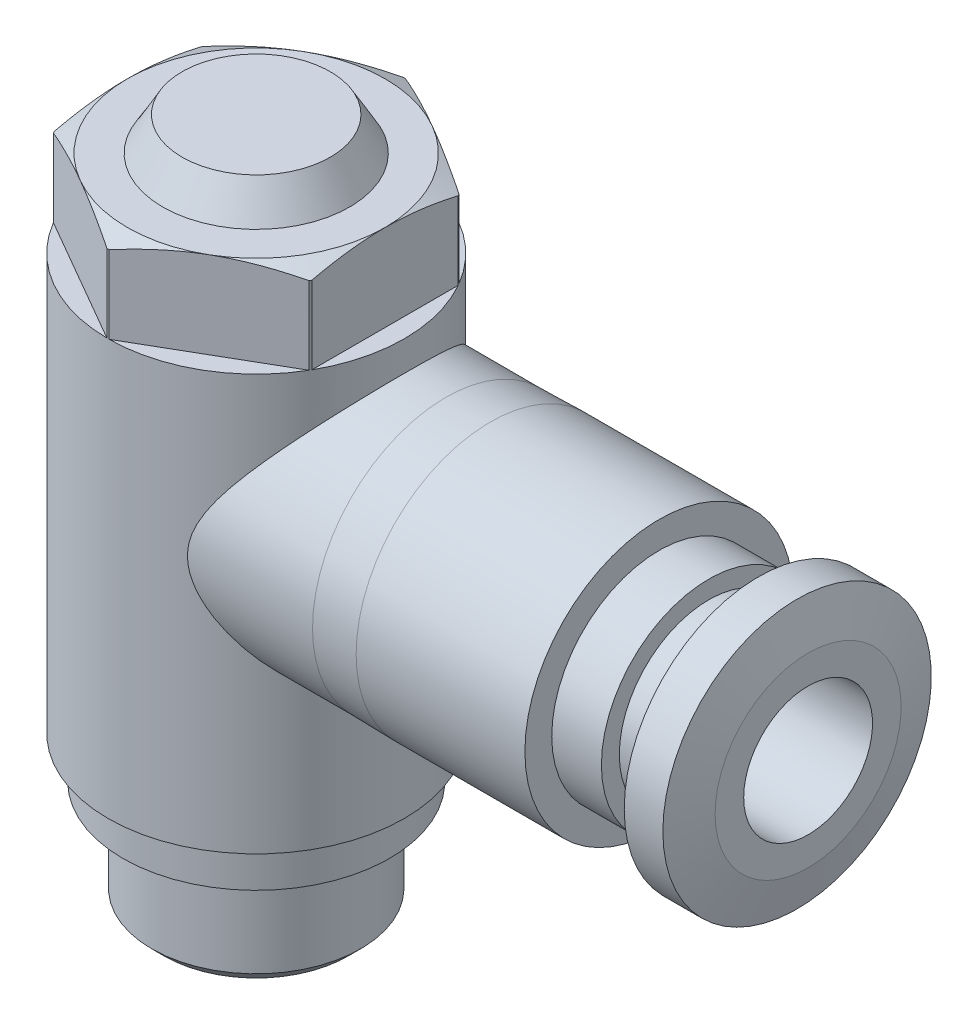
SolidWorks part; units mm, degrees
material "Kunststoff schwarz"
ref_plane "Vorne" through (0, 0, 0) normal (0, 0, 1) x (1, 0, 0)
ref_plane "Oben" through (0, 0, 0) normal (0, 1, 0) x (1, 0, 0)
ref_plane "Rechts" through (0, 0, 0) normal (1, 0, 0) x (0, 0, -1)
ref_plane "Ebene1" through (0, 0, 0) normal (0, 0, 1) x (1, 0, 0)
sketch "Skizze1" plane through (0, 0, 0) normal (0, 0, 1) x (1, 0, 0)
  line L0 (0, 13.2) -> (3.45, 13.2)
  line L1 (3.45, 13.2) -> (4.3508, 11.6398)
  line L2 (4.3508, 11.6398) -> (6, 11.6398)
  line L3 (6, 11.6398) -> (6.9, 11.2201)
  line L4 (6.9, 11.2201) -> (6.9, -11.7429)
  line L5 (6.9, -11.7429) -> (6.21, -11.7429)
  line L6 (6.21, -11.7429) -> (6.21, -13.7)
  line L7 (6.21, -13.7) -> (4.864, -13.7)
  line L8 (4.864, -13.7) -> (4.864, -18.019)
  line L9 (4.864, -18.019) -> (4.283, -18.6)
  line L10 (4.283, -18.6) -> (3.648, -18.6)
  line L11 (3.648, -18.6) -> (3.648, -8.872)
  line L12 (3.648, -8.872) -> (0, -8.872)
  line L13 (0, -8.872) -> (0, 13.2)
  line L14 (0, -18.6) -> (0, 13.2) construction
revolve "Rotation1" add sketch "Skizze1" angle 360 about L14
ref_plane "Ebene2" through (0, 11.6398, 0) normal (0, 1, 0) x (-1, 0, 0)
sketch "Skizze2" plane through (0, 11.6398, 0) normal (0, 1, 0) x (-1, 0, 0)
  line L0 (7.8, -4.5033) -> (7.8, 4.5033)
  line L1 (7.8, 4.5033) -> (0, 9.0067)
  line L2 (0, 9.0067) -> (-7.8, 4.5033)
  line L3 (-7.8, 4.5033) -> (-7.8, -4.5033)
  line L4 (-7.8, -4.5033) -> (-0.05, -8.9778)
  line L5 (-0.05, -8.9778) -> (-0.05, -6.8993)
  line L6 (-0.05, -6.8993) -> (-6, -3.4641)
  line L7 (-6, -3.4641) -> (-6, 3.4641)
  line L8 (-6, 3.4641) -> (0, 6.9282)
  line L9 (0, 6.9282) -> (6, 3.4641)
  line L10 (6, 3.4641) -> (6, -3.4641)
  line L11 (6, -3.4641) -> (0, -6.9282)
  line L12 (0, -6.9282) -> (0, -9.0067)
  line L13 (0, -9.0067) -> (7.8, -4.5033)
extrude "Linear austragen1" cut sketch "Skizze2" against normal blind 4.035 and the other way blind 4.035
ref_plane "Ebene3" through (0, 0, 0) normal (0, 0, 1) x (1, 0, 0)
sketch "Skizze3" plane through (0, 0, 0) normal (0, 0, 1) x (1, 0, 0)
  line L0 (0, 0) -> (0, 6.21)
  line L1 (0, 6.21) -> (8.832, 6.21)
  line L2 (8.832, 6.21) -> (10.902, 6.25)
  line L3 (10.902, 6.25) -> (18.761, 6.25)
  line L4 (18.761, 6.25) -> (18.761, 5)
  line L5 (18.761, 5) -> (21.074, 5)
  line L6 (21.074, 5) -> (21.074, 4.1667)
  line L7 (21.074, 4.1667) -> (23.387, 4.1667)
  line L8 (23.387, 4.1667) -> (23.387, 6.25)
  line L9 (23.387, 6.25) -> (25.186, 6.25)
  line L10 (25.186, 6.25) -> (25.7, 4.3317)
  line L11 (25.7, 4.3317) -> (25.7, 3)
  line L12 (25.7, 3) -> (7.7, 3)
  line L13 (7.7, 3) -> (7.7, 0)
  line L14 (7.7, 0) -> (0, 0)
  line L15 (25.7, 0) -> (0, 0) construction
revolve "Rotation2" add sketch "Skizze3" angle 360 about L15
